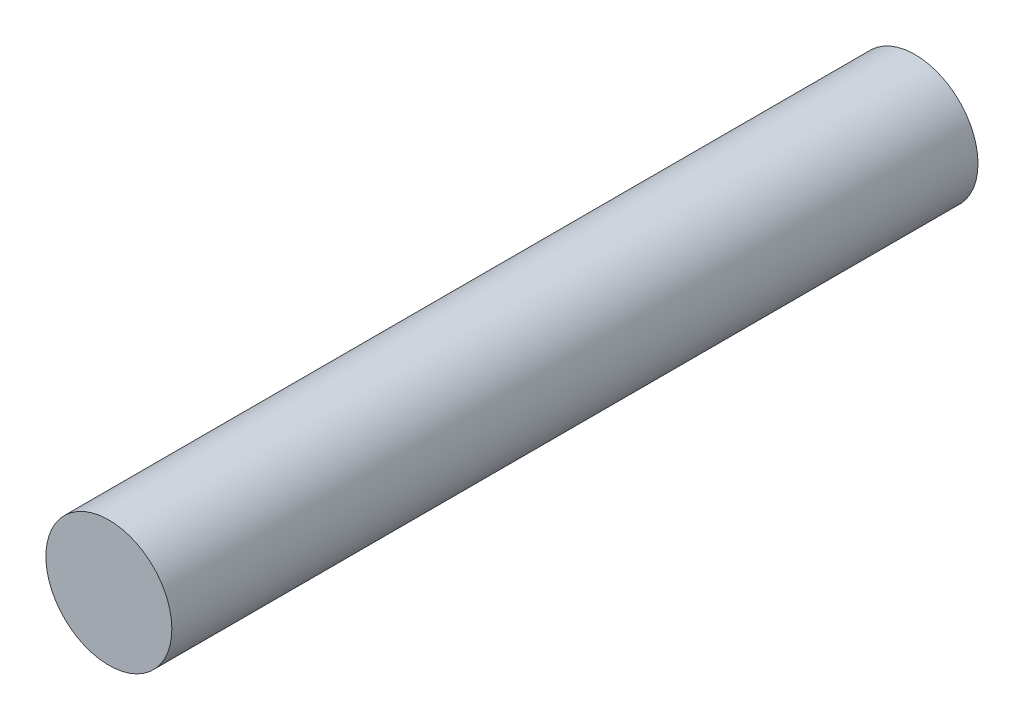
SolidWorks part; units mm, degrees
ref_plane "Front Plane" through (0, 0, 0) normal (0, 0, 1) x (1, 0, 0)
ref_plane "Top Plane" through (0, 0, 0) normal (0, 1, 0) x (1, 0, 0)
ref_plane "Right Plane" through (0, 0, 0) normal (1, 0, 0) x (0, 0, -1)
sketch "Sketch1" plane through (0, 0, 0) normal (0, 0, 1) x (1, 0, 0)
  circle A0 centre (0, 0) radius 2.5
  dimension "D1" = 5
extrude "Boss-Extrude1" add sketch "Sketch1" along normal blind 32
